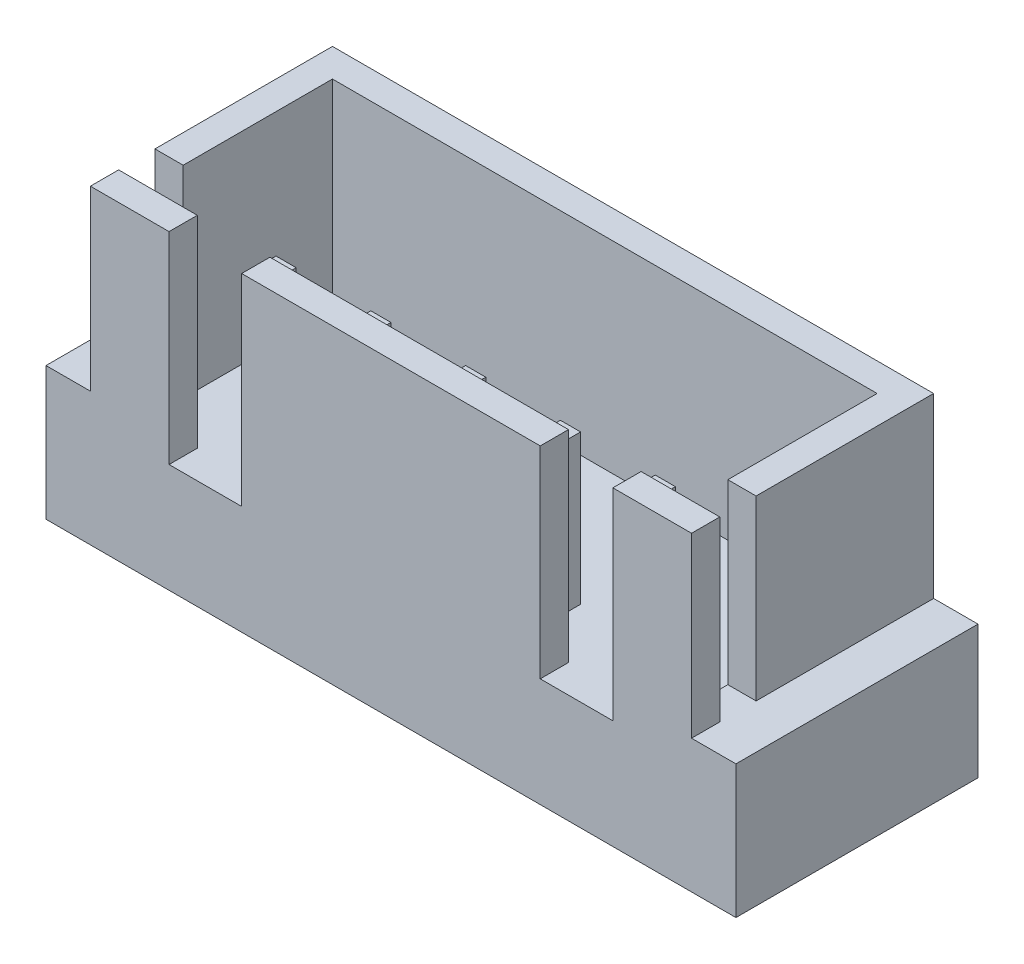
SolidWorks part; units mm, degrees
ref_plane "Front" through (0, 0, 0) normal (0, 0, 1) x (1, 0, 0)
ref_plane "Top" through (0, 0, 0) normal (0, 1, 0) x (1, 0, 0)
ref_plane "Right" through (0, 0, 0) normal (1, 0, 0) x (0, 0, -1)
sketch "Sketch1" plane through (0, 0, 0) normal (0, 1, 0) x (1, 0, 0)
  line L0 (0, 3) -> (0, 0) construction
  line L1 (-8.55, 3) -> (8.55, 3)
  line L2 (-8.55, 3) -> (-8.55, -3)
  line L3 (-8.55, -3) -> (8.55, -3)
  line L4 (8.55, 3) -> (8.55, -3)
  line L5 (0, 0) -> (8.55, 0) construction
  dimension "D1" = 17.1
  dimension "D2" = 6
extrude "Boss-Extrude1" add sketch "Sketch1" along normal blind 7.7
sketch "Sketch2" plane through (0, 7.7, 0) normal (0, 1, 0) x (1, 0, 0)
  line L1 (-6.75, 2.3) -> (6.75, 2.3)
  line L2 (-6.75, 2.3) -> (-6.75, -2.3)
  line L3 (-6.75, -2.3) -> (6.75, -2.3)
  line L4 (6.75, 2.3) -> (6.75, -2.3)
  line L5 (0, 3) -> (0, 0) construction
  line L6 (0, 0) -> (4.118, 0) construction
  line L7 (0, 0) -> (8.55, 0) construction
  dimension "D1" = 13.5
  dimension "D2" = 4.6
extrude "Cut-Extrude1" cut sketch "Sketch2" against normal blind 5
sketch "Sketch3" plane through (0, 7.7, 0) normal (0, 1, 0) x (1, 0, 0)
  line L0 (-8.55, -3) -> (8.55, -3) construction
  line L1 (-8.55, 3) -> (-7.45, 3)
  line L2 (-8.55, 3) -> (-8.55, -3)
  line L3 (-8.55, -3) -> (-7.45, -3)
  line L4 (-7.45, 3) -> (-7.45, -3)
  line L6 (8.55, 3) -> (7.45, 3)
  line L7 (8.55, 3) -> (8.55, -3)
  line L8 (8.55, -3) -> (7.45, -3)
  line L9 (7.45, 3) -> (7.45, -3)
  dimension "D1" = 1.1
extrude "Cut-Extrude2" cut sketch "Sketch3" against normal blind 4.4
sketch "Sketch4" plane through (0, 7.7, 0) normal (0, 1, 0) x (1, 0, 0)
  line L0 (0, 0) -> (0, -3) construction
  line L1 (-8.55, -3) -> (8.55, -3) construction
  line L2 (-6.75, -2.3) -> (6.75, -2.3) construction
  line L3 (-5.5, -2.3) -> (-3.7, -2.3)
  line L4 (-5.5, -2.3) -> (-5.5, -3)
  line L5 (-5.5, -3) -> (-3.7, -3)
  line L6 (-3.7, -2.3) -> (-3.7, -3)
  line L7 (-7.45, -3) -> (-7.45, 3) construction
  line L8 (3.7, -2.3) -> (3.7, -3)
  line L9 (5.5, -3) -> (3.7, -3)
  line L10 (5.5, -2.3) -> (5.5, -3)
  line L11 (5.5, -2.3) -> (3.7, -2.3)
  dimension "D1" = 1.95
  dimension "D2" = 1.8
extrude "Cut-Extrude3" cut sketch "Sketch4" against normal up to surface (5 mm away) up to face at (0, 2.7, 0)
sketch "Sketch5" plane through (0, 7.7, 0) normal (0, 1, 0) x (1, 0, 0)
  line L0 (-7.45, -3) -> (-7.45, 3) construction
  line L1 (-7.45, -1.4) -> (7.45, -1.4)
  line L2 (-7.45, -1.4) -> (-7.45, -2.3)
  line L3 (-7.45, -2.3) -> (7.45, -2.3)
  line L4 (7.45, -1.4) -> (7.45, -2.3)
  line L5 (7.45, 3) -> (7.45, -3) construction
  line L6 (5.5, -2.3) -> (6.75, -2.3) construction
  dimension "D1" = 0.9
extrude "Cut-Extrude4" cut sketch "Sketch5" against normal up to surface (4.4 mm away) up to face at (8, 3.3, 0)
sketch "Sketch6" plane through (0, 2.7, 0) normal (0, 1, 0) x (1, 0, 0)
  line L0 (-7.45, -1.4) -> (7.45, -1.4) construction
  line L1 (-0.25, -0.9) -> (0.25, -0.9)
  line L2 (-0.25, -0.9) -> (-0.25, -1.4)
  line L3 (-0.25, -1.4) -> (0.25, -1.4)
  line L4 (0.25, -0.9) -> (0.25, -1.4)
  line L5 (0, 0) -> (0, 4.0905) construction
  line L6 (-2.6, -0.9) -> (-2.1, -0.9)
  line L7 (-2.6, -0.9) -> (-2.6, -1.4)
  line L8 (-2.6, -1.4) -> (-2.1, -1.4)
  line L9 (-2.1, -0.9) -> (-2.1, -1.4)
  line L10 (2.1, -0.9) -> (2.1, -1.4)
  line L11 (2.6, -1.4) -> (2.1, -1.4)
  line L12 (2.6, -0.9) -> (2.6, -1.4)
  line L13 (2.6, -0.9) -> (2.1, -0.9)
  line L14 (4.45, -0.9) -> (4.45, -1.4)
  line L15 (-4.95, -0.9) -> (-4.45, -0.9)
  line L16 (-4.95, -0.9) -> (-4.95, -1.4)
  line L17 (-4.95, -1.4) -> (-4.45, -1.4)
  line L18 (-4.45, -0.9) -> (-4.45, -1.4)
  line L19 (4.95, -1.4) -> (4.45, -1.4)
  line L20 (4.95, -0.9) -> (4.95, -1.4)
  line L21 (4.95, -0.9) -> (4.45, -0.9)
  point P14 (0, -0.9)
  dimension "D1" = 1.85
  dimension "D2" = 0.5
  dimension "D3" = 1.85
extrude "Boss-Extrude2" add sketch "Sketch6" along normal blind 3.7
